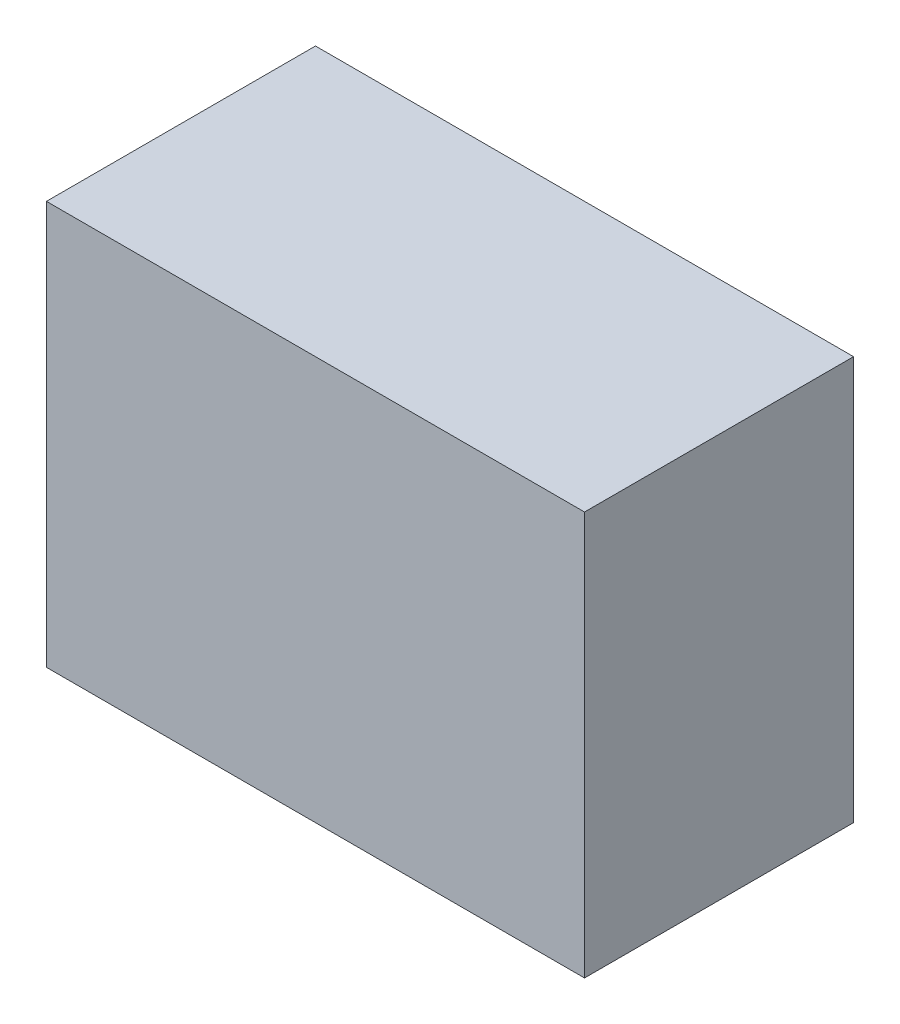
SolidWorks part; units mm, degrees
ref_plane "Front Plane" through (0, 0, 0) normal (0, 0, 1) x (1, 0, 0)
ref_plane "Top Plane" through (0, 0, 0) normal (0, 1, 0) x (1, 0, 0)
ref_plane "Right Plane" through (0, 0, 0) normal (1, 0, 0) x (0, 0, -1)
sketch "Sketch1" plane through (0, 0, 0) normal (0, 1, 0) x (1, 0, 0)
  line L1 (4, -2) -> (-4, -2)
  line L2 (4, -2) -> (4, 2)
  line L3 (4, 2) -> (-4, 2)
  line L4 (-4, -2) -> (-4, 2)
  line L5 (4, -2) -> (-4, 2) construction
  line L6 (4, 2) -> (-4, -2) construction
  point P1 (0, 0)
  dimension "D1" = 8
  dimension "D2" = 4
extrude "Boss-Extrude1" add sketch "Sketch1" along normal blind 6
